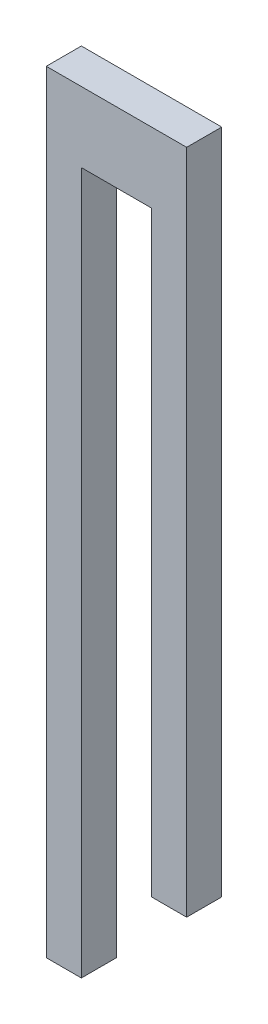
SolidWorks part; units mm, degrees
ref_plane "Front Plane" through (0, 0, 0) normal (0, 0, 1) x (1, 0, 0)
ref_plane "Top Plane" through (0, 0, 0) normal (0, 1, 0) x (1, 0, 0)
ref_plane "Right Plane" through (0, 0, 0) normal (1, 0, 0) x (0, 0, -1)
sketch "Sketch2" plane through (0, 0, 0) normal (0, 1, 0) x (1, 0, 0)
  line L1 (10, -2.5) -> (-10, -2.5)
  line L2 (10, -2.5) -> (10, 2.5)
  line L3 (10, 2.5) -> (-10, 2.5)
  line L4 (-10, -2.5) -> (-10, 2.5)
  line L5 (10, -2.5) -> (-10, 2.5) construction
  line L6 (10, 2.5) -> (-10, -2.5) construction
  point P0 (0, 0)
  dimension "D1" = 5
  dimension "D2" = 20
extrude "Boss-Extrude1" add sketch "Sketch2" along normal blind 10
sketch "Sketch5" plane through (0, 0, 0) normal (0, 1, 0) x (1, 0, 0)
  line L0 (-10, 0) -> (10, 0) construction
  line L1 (-10, 2.5) -> (-10, -2.5) construction
  line L2 (10, -2.5) -> (10, 2.5) construction
  line L3 (10, 2.5) -> (-10, 2.5) construction
  line L4 (-10, -2.5) -> (-5, -2.5)
  line L5 (-10, -2.5) -> (-10, 2.5)
  line L6 (-10, 2.5) -> (-5, 2.5)
  line L7 (-5, -2.5) -> (-5, 2.5)
  line L8 (0, -5.5369) -> (0, 7.8324) construction
  line L9 (10, -2.5) -> (10, 2.5)
  line L10 (10, 2.5) -> (5, 2.5)
  line L11 (5, -2.5) -> (5, 2.5)
  line L12 (10, -2.5) -> (5, -2.5)
  dimension "D1" = 5
extrude "Boss-Extrude2" add sketch "Sketch5" against normal blind 100 contours L4 L7 L6 L5
sketch "Sketch6" plane through (0, 0, 0) normal (0, -1, 0) x (1, 0, 0)
  line L0 (10, -2.5) -> (-5, -2.5) construction
  line L1 (10, 2.5) -> (5, 2.5)
  line L2 (10, 2.5) -> (10, -2.5)
  line L3 (10, -2.5) -> (5, -2.5)
  line L4 (5, 2.5) -> (5, -2.5)
  dimension "D1" = 5
extrude "Boss-Extrude3" add sketch "Sketch6" along normal blind 85
